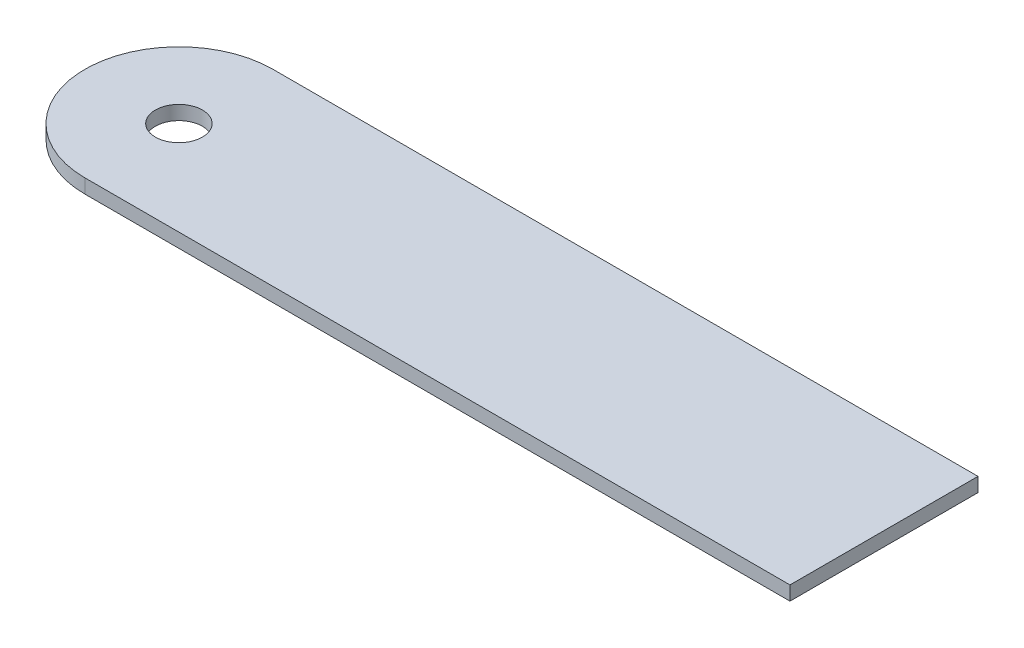
SolidWorks part; units mm, degrees
material "Plain Carbon Steel"
ref_plane "Front Plane" through (0, 0, 0) normal (0, 0, 1) x (1, 0, 0)
ref_plane "Top Plane" through (0, 0, 0) normal (0, 1, 0) x (1, 0, 0)
ref_plane "Right Plane" through (0, 0, 0) normal (1, 0, 0) x (0, 0, -1)
sketch "Sketch1" plane through (0, 0, 0) normal (0, 1, 0) x (1, 0, 0)
  line L1 (-75, -20) -> (75, -20)
  line L2 (-75, -20) -> (-75, 20)
  line L3 (-75, 20) -> (75, 20)
  line L4 (75, -20) -> (75, 20)
  line L5 (-75, -20) -> (75, 20) construction
  line L6 (-75, 20) -> (75, -20) construction
  circle A0 centre (-75, 0) radius 20
  circle A1 centre (-75, 0) radius 5
  point P0 (0, 0)
  dimension "D3" = 10
  dimension "D1" = 150
  dimension "D2" = 40
extrude "Boss-Extrude1" add sketch "Sketch1" along normal blind 3 contours A1 L2 A0 | A1 L2 A0 | A0 L1 L4 L3
